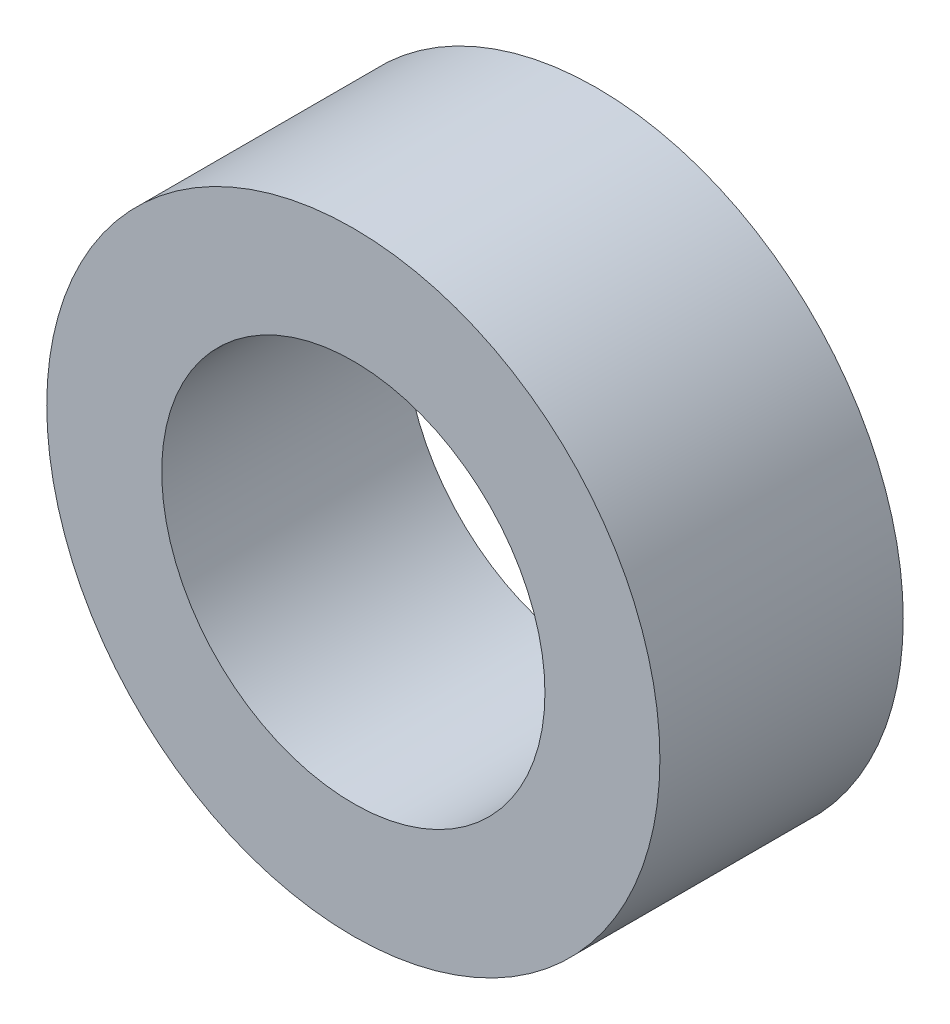
SolidWorks part; units mm, degrees
ref_plane "Front Plane" through (0, 0, 0) normal (0, 0, 1) x (1, 0, 0)
ref_plane "Top Plane" through (0, 0, 0) normal (0, 1, 0) x (1, 0, 0)
ref_plane "Right Plane" through (0, 0, 0) normal (1, 0, 0) x (0, 0, -1)
sketch "Sketch1" plane through (0, 0, 0) normal (0, 0, 1) x (1, 0, 0)
  line L0 (-4.9097, 0) -> (3.1623, 0) construction
  circle A0 centre (0, 0) radius 4
  dimension "D1" = 8
extrude "Boss-Extrude1" add sketch "Sketch1" along normal blind 3.175
sketch "Sketch2" plane through (0, 0, 3.175) normal (0, 0, 1) x (1, 0, 0)
  circle A0 centre (0, 0) radius 2.5
  dimension "D1" = 5
extrude "Cut-Extrude1" cut sketch "Sketch2" against normal through all
